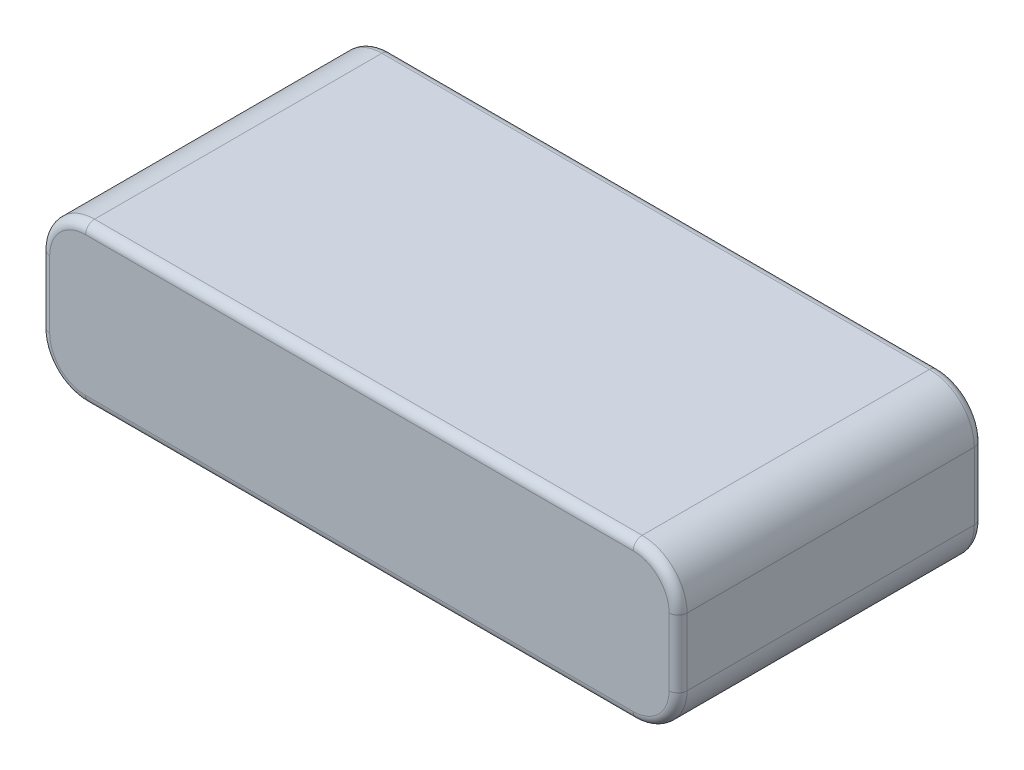
SolidWorks part; units mm, degrees
ref_plane "Front Plane" through (0, 0, 0) normal (0, 0, 1) x (1, 0, 0)
ref_plane "Top Plane" through (0, 0, 0) normal (0, 1, 0) x (1, 0, 0)
ref_plane "Right Plane" through (0, 0, 0) normal (1, 0, 0) x (0, 0, -1)
sketch "Sketch1" plane through (0, 0, 0) normal (0, 1, 0) x (1, 0, 0)
  line L1 (-35.5, -17) -> (35.5, -17)
  line L2 (-35.5, -17) -> (-35.5, 17)
  line L3 (-35.5, 17) -> (35.5, 17)
  line L4 (35.5, -17) -> (35.5, 17)
  line L5 (-35.5, -17) -> (35.5, 17) construction
  line L6 (-35.5, 17) -> (35.5, -17) construction
  point P0 (0, 0)
  dimension "D1" = 71
  dimension "D2" = 34
extrude "Boss-Extrude1" add sketch "Sketch1" along normal blind 17.5
fillet "Fillet2" radius 5 4 edges at (-35.5, 0, 0) (35.5, 0, 0) (35.5, 17.5, 0) (-35.5, 17.5, 0)
fillet "Fillet3" radius 1 16 edges at (-34.0355, 16.0355, 17) (0, 17.5, 17) (34.0355, 16.0355, 17) (35.5, 8.75, 17) (34.0355, 1.4645, 17) (0, 0, 17) (-34.0355, 1.4645, 17) (-35.5, 8.75, 17) (34.0355, 1.4645, -17) (35.5, 8.75, -17) (34.0355, 16.0355, -17) (0, 17.5, -17) (-34.0355, 16.0355, -17) (-35.5, 8.75, -17) (-34.0355, 1.4645, -17) (0, 0, -17)
